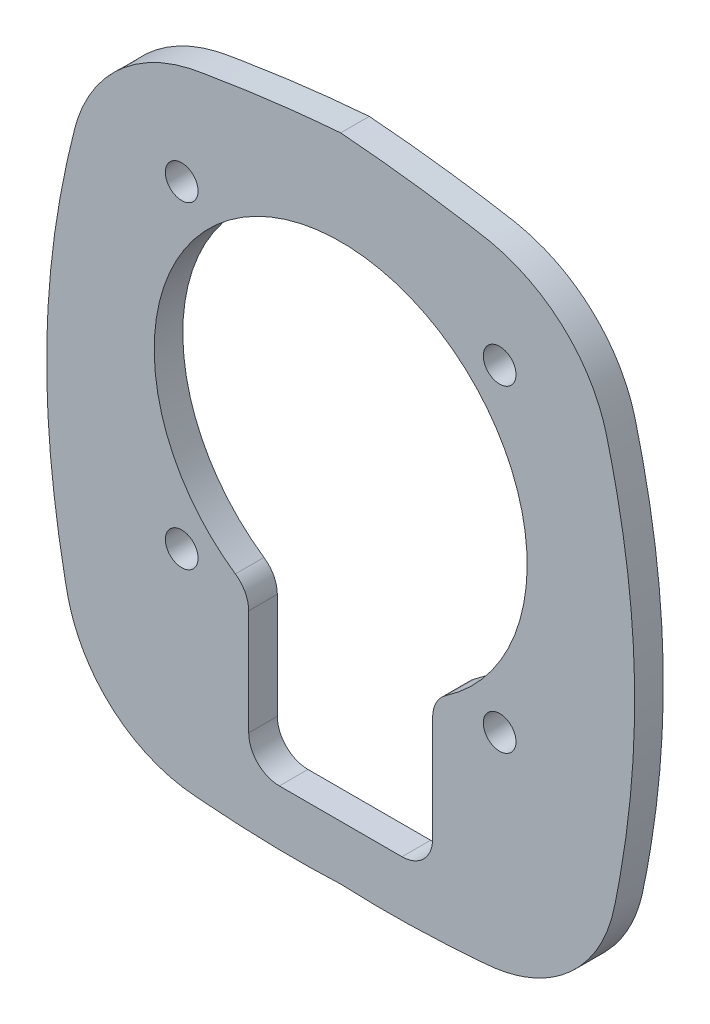
SolidWorks part; units mm, degrees
material "Фанера"
ref_plane "Front Plane" through (0, 0, 0) normal (0, 0, 1) x (1, 0, 0)
ref_plane "Top Plane" through (0, 0, 0) normal (0, 1, 0) x (1, 0, 0)
ref_plane "Right Plane" through (0, 0, 0) normal (1, 0, 0) x (0, 0, -1)
sketch "Эскиз1" plane through (0, 0, 0) normal (0, 0, 1) x (1, 0, 0)
  line L0 (-33.6095, 103.6369) -> (54.1763, 103.6369) construction
  line L1 (0, 136.9945) -> (0, 54.1012) construction
  line L2 (-17.5232, 86.1137) -> (17.4833, 121.1202) construction
  line L4 (-6, 72.7605) -> (6, 72.7605)
  line L5 (-9, 75.7605) -> (-9, 86.0995)
  line L7 (9, 75.7605) -> (9, 86.0995)
  line L8 (-9, 72.7605) -> (0, 85.3869) construction
  line L9 (0, 85.3869) -> (9, 72.7605) construction
  circle A0 centre (15.5563, 119.1933) radius 1.6
  circle A2 centre (15.5563, 88.0806) radius 1.6
  circle A3 centre (0, 103.6369) radius 5.3081 construction
  circle A4 centre (-15.5563, 88.0806) radius 1.6
  circle A5 centre (-15.5563, 119.1933) radius 1.6
  arc A6 (10.3059, 88.5754) -> (-10.3059, 88.5754) centre (0, 103.6369) ccw
  arc A7 (9, 86.0995) -> (10.3059, 88.5754) centre (12, 86.0995) cw
  arc A8 (-9, 86.0995) -> (-10.3059, 88.5754) centre (-12, 86.0995) ccw
  arc A9 (6, 72.7605) -> (9, 75.7605) centre (6, 75.7605) ccw
  arc A10 (-6, 72.7605) -> (-9, 75.7605) centre (-6, 75.7605) cw
  spline S2 degree 3 poles (0, 131.1062) (-0.3702, 131.0763) (-1.1028, 131.0172) (-2.1891, 130.9196) (-3.4436, 130.7985) (-4.8817, 130.6463) (-6.503, 130.4563) (-8.125, 130.2474) (-9.7417, 130.0206) (-11.3628, 129.775) (-12.676, 129.562) (-13.6897, 129.3901) (-14.4132, 129.2646) (-15.1596, 129.0944) (-15.9282, 128.8804) (-16.7152, 128.6164) (-17.5163, 128.2986) (-18.3267, 127.9229) (-19.728, 127.1697) (-21.748, 125.7276) (-23.5677, 123.7) (-24.6127, 122.0113) (-25.1013, 121.049) (-25.4626, 120.2251) (-25.7389, 119.4608) (-25.9468, 118.7675) (-26.0817, 118.2397) (-26.2129, 117.7174) (-26.5508, 116.3391) (-27.0624, 114.0664) (-27.6532, 110.9226) (-28.1312, 107.7137) (-28.4753, 104.5458) (-28.6991, 101.2935) (-28.8206, 96.9974) (-28.6815, 92.7434) (-28.3105, 88.4657) (-28.0114, 86.0398) (-27.6872, 83.8215) (-27.4469, 82.3517) (-27.1704, 80.8223) (-26.9644, 79.7639) (-26.7959, 78.9056) (-26.6398, 78.2276) (-26.4962, 77.7067) (-26.3157, 77.1264) (-26.0804, 76.4742) (-25.653, 75.4713) (-25.0212, 74.2848) (-23.7978, 72.5158) (-22.2749, 70.9806) (-20.5079, 69.748) (-19.0733, 68.9835) (-17.5657, 68.3965) (-16.3741, 68.0858) (-15.5407, 67.9319) (-15.0588, 67.8587) (-14.5432, 67.7975) (-13.9938, 67.7521) (-13.4123, 67.7047) (-12.6889, 67.6502) (-11.8043, 67.5891) (-10.7388, 67.5241) (-8.9321, 67.4292) (-6.9506, 67.36) (-4.8154, 67.3354) (-3.1864, 67.3427) (-1.5776, 67.3747) (-0.5086, 67.4211) (0, 67.4432) knots 0 0 0 0 0.010771 0.021313 0.031628 0.047323 0.06325 0.078966 0.094746 0.110593 0.126514 0.133325 0.14041 0.147806 0.155515 0.163537 0.171867 0.180498 0.189424 0.217986 0.251993 0.267593 0.275472 0.283275 0.293668 0.299019 0.30426 0.309463 0.314637 0.345412 0.377007 0.407382 0.439473 0.469388 0.501899 0.564079 0.59267 0.626404 0.634941 0.657685 0.669589 0.680012 0.688953 0.694954 0.700182 0.70462 0.712574 0.720276 0.736225 0.751452 0.782552 0.798228 0.813816 0.829575 0.845041 0.849441 0.854152 0.859171 0.864496 0.870136 0.876092 0.885532 0.895852 0.907048 0.937998 0.953339 0.968971 0.985238 1 1 1 1
  spline S3 degree 3 poles (0, 67.4432) (0.2498, 67.4316) (0.7627, 67.4079) (1.5522, 67.3807) (2.3816, 67.3592) (3.4924, 67.3408) (4.8609, 67.3356) (7.0177, 67.3614) (9.2063, 67.4395) (11.3606, 67.5592) (12.7428, 67.6525) (13.8286, 67.7384) (14.6702, 67.8067) (15.4337, 67.9108) (16.4372, 68.0976) (17.7023, 68.4416) (19.1991, 69.0422) (20.6198, 69.8178) (22.3705, 71.0635) (23.8791, 72.6123) (25.088, 74.3955) (25.7081, 75.5866) (26.1255, 76.5907) (26.3812, 77.3194) (26.6103, 78.0983) (26.7713, 78.7963) (26.904, 79.4609) (27.0194, 80.041) (27.1412, 80.6774) (27.2695, 81.37) (27.4848, 82.582) (27.6985, 83.8954) (28.021, 86.1095) (28.3221, 88.5758) (28.6884, 92.8624) (28.8217, 97.1322) (28.6919, 101.4443) (28.4611, 104.7035) (28.1104, 107.8744) (27.6255, 111.0861) (27.0271, 114.2367) (26.4904, 116.6008) (26.103, 118.158) (25.9212, 118.8668) (25.6776, 119.6395) (25.1101, 121.1479) (23.8327, 123.4328) (21.623, 125.8387) (19.5853, 127.2596) (18.1767, 127.9969) (17.3651, 128.3626) (16.5634, 128.671) (15.7765, 128.926) (15.0085, 129.1319) (14.2626, 129.2936) (13.5403, 129.415) (12.5345, 129.5857) (11.2349, 129.7948) (9.1036, 130.1162) (6.9662, 130.4026) (4.8289, 130.6521) (3.2288, 130.8207) (1.6218, 130.9738) (0.5464, 131.0616) (0, 131.1062) knots 0 0 0 0 0.007253 0.014889 0.022909 0.031315 0.04711 0.062594 0.093869 0.110611 0.125167 0.134046 0.142201 0.149649 0.156381 0.171796 0.187581 0.203049 0.218623 0.249784 0.265042 0.281007 0.288624 0.296566 0.303391 0.312159 0.31733 0.323048 0.329311 0.33612 0.343475 0.365012 0.374709 0.408363 0.437047 0.499467 0.532106 0.562131 0.594201 0.6246 0.656308 0.687188 0.69489 0.702849 0.708403 0.718376 0.749562 0.783616 0.812211 0.821107 0.82971 0.838012 0.846006 0.85369 0.861061 0.868129 0.874931 0.890648 0.906302 0.937441 0.953185 0.968707 0.984102 1 1 1 1
  spline S6 degree 3 poles (0.0004, 131.9089) (-0.0159, 131.9075) (-0.0428, 131.9054) (-2.1924, 131.732) (-5.4202, 131.415) (-9.6929, 130.8482) (-12.3658, 130.4183) (-14.508, 130.0793) (-16.7336, 129.5269) (-19.3432, 128.4151) (-22.1553, 126.4452) (-24.4752, 123.8994) (-25.8878, 121.4202) (-26.6662, 119.256) (-27.1828, 117.1196) (-27.7959, 114.4843) (-28.4047, 111.2734) (-28.8952, 108.0459) (-29.3767, 103.717) (-29.6542, 98.2761) (-29.4905, 92.8306) (-29.1184, 88.4954) (-28.7207, 85.2562) (-28.3032, 82.5756) (-27.909, 80.4309) (-27.6123, 78.849) (-27.207, 77.1816) (-26.3998, 75.0513) (-24.9514, 72.5746) (-22.5477, 70.0835) (-19.6247, 68.246) (-16.9139, 67.3239) (-14.6389, 66.9838) (-12.4813, 66.8357) (-9.773, 66.6563) (-6.5186, 66.5443) (-3.2584, 66.5254) (-1.0865, 66.5953) (-0.0011, 66.6424) knots -0.000628 -0.000628 -0.000628 -0.000628 -0.000157 0.000157 0.06189 0.093149 0.124407 0.140037 0.155666 0.186925 0.218184 0.249442 0.280701 0.296331 0.31196 0.343219 0.374478 0.405736 0.436995 0.499513 0.56203 0.593289 0.624548 0.655807 0.671436 0.687065 0.702695 0.718324 0.749583 0.780842 0.812101 0.843359 0.858989 0.874618 0.905877 0.937136 0.968394 0.999653 0.999653 0.999653 0.999653 construction
  spline S7 degree 3 poles (-0.0011, 66.6424) (2.1695, 66.5419) (5.4339, 66.5053) (9.772, 66.6566) (12.4817, 66.8357) (14.6377, 66.9839) (16.9129, 67.3235) (19.6236, 68.2456) (22.5465, 70.0825) (24.9503, 72.573) (26.399, 75.0504) (27.2066, 77.1787) (27.611, 78.8488) (27.9094, 80.43) (28.3025, 82.573) (28.7205, 85.2543) (29.1182, 88.4931) (29.4904, 92.8281) (29.6543, 98.2733) (29.3769, 103.7139) (28.8956, 108.0425) (28.4053, 111.2701) (27.7968, 114.4803) (27.1835, 117.1167) (26.6676, 119.2508) (25.8901, 121.4161) (24.4735, 123.9025) (22.1547, 126.4453) (19.3425, 128.4158) (16.7315, 129.5274) (14.5094, 130.0792) (12.3645, 130.4186) (9.6926, 130.8481) (5.4197, 131.4155) (2.1928, 131.7298) (0.0435, 131.9053) (0.0167, 131.9075) (0.0004, 131.9089) knots 0.000347 0.000347 0.000347 0.000347 0.062864 0.094123 0.125382 0.141011 0.156641 0.187899 0.219158 0.250417 0.281676 0.297305 0.312935 0.328564 0.344193 0.375452 0.406711 0.43797 0.500487 0.563005 0.594264 0.625522 0.656781 0.68804 0.703669 0.719299 0.750558 0.781816 0.813075 0.844334 0.859963 0.875593 0.906852 0.93811 0.999843 1.000157 1.000628 1.000628 1.000628 1.000628 construction
  point P21 (0, 85.3869)
  point P26 (0, 0)
  point P31 (-9, 87.7605)
  dimension "D2" = 3.2
  dimension "D4" = 36.5
  dimension "D7" = 3
  dimension "D1" = 45
  dimension "D3" = 22
  dimension "D5" = 18
  dimension "D6" = 15
extrude "Бобышка-Вытянуть1" add sketch "Эскиз1" along normal mid plane 2.8
